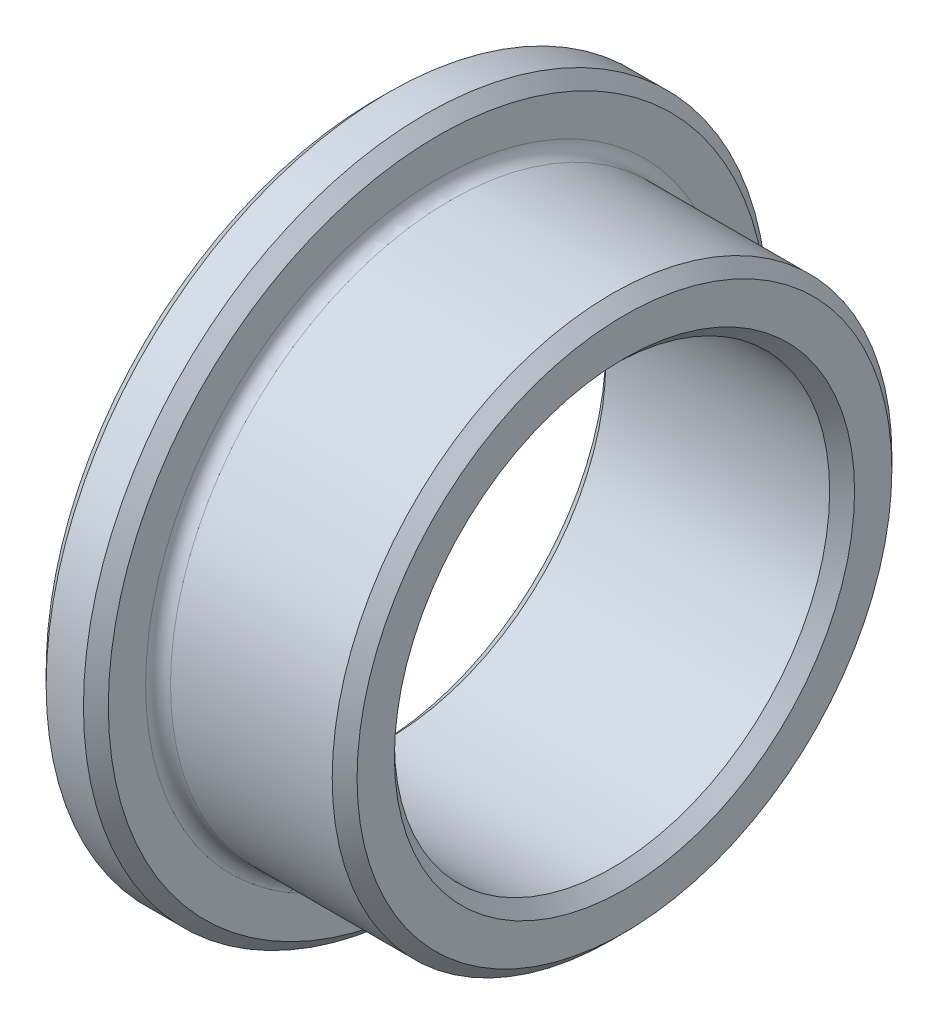
SolidWorks part; units mm, degrees
material "Phosphor bronze 10% D, UNS C52400"
ref_plane "Front Plane" through (0, 0, 0) normal (0, 0, 1) x (1, 0, 0)
ref_plane "Top Plane" through (0, 0, 0) normal (0, 1, 0) x (1, 0, 0)
ref_plane "Right Plane" through (0, 0, 0) normal (1, 0, 0) x (0, 0, -1)
sketch "Sketch1" plane through (0, 0, 0) normal (0, 0, 1) x (1, 0, 0)
  line L0 (0, 17.5) -> (20, 17.5)
  line L1 (20, 17.5) -> (20, 22.5)
  line L2 (20, 22.5) -> (5, 22.5)
  line L3 (5, 22.5) -> (5, 27.5)
  line L4 (5, 27.5) -> (0, 27.5)
  line L5 (0, 27.5) -> (0, 17.5)
  line L6 (0, 0) -> (44.8454, 0) construction
  dimension "D1" = 35
  dimension "D2" = 5
  dimension "D3" = 55
  dimension "D4" = 20
  dimension "D5" = 45
revolve "Revolve1" add sketch "Sketch1" angle 360 about L6
chamfer "Chamfer1" distance 1 angle 45 5 edges at (0, 0, 17.5) (20, 0, 17.5) (5, 0, 27.5) (0, 0, 27.5) (20, 0, 22.5)
fillet "Fillet1" radius 1 1 edges at (5, 0, 22.5)
